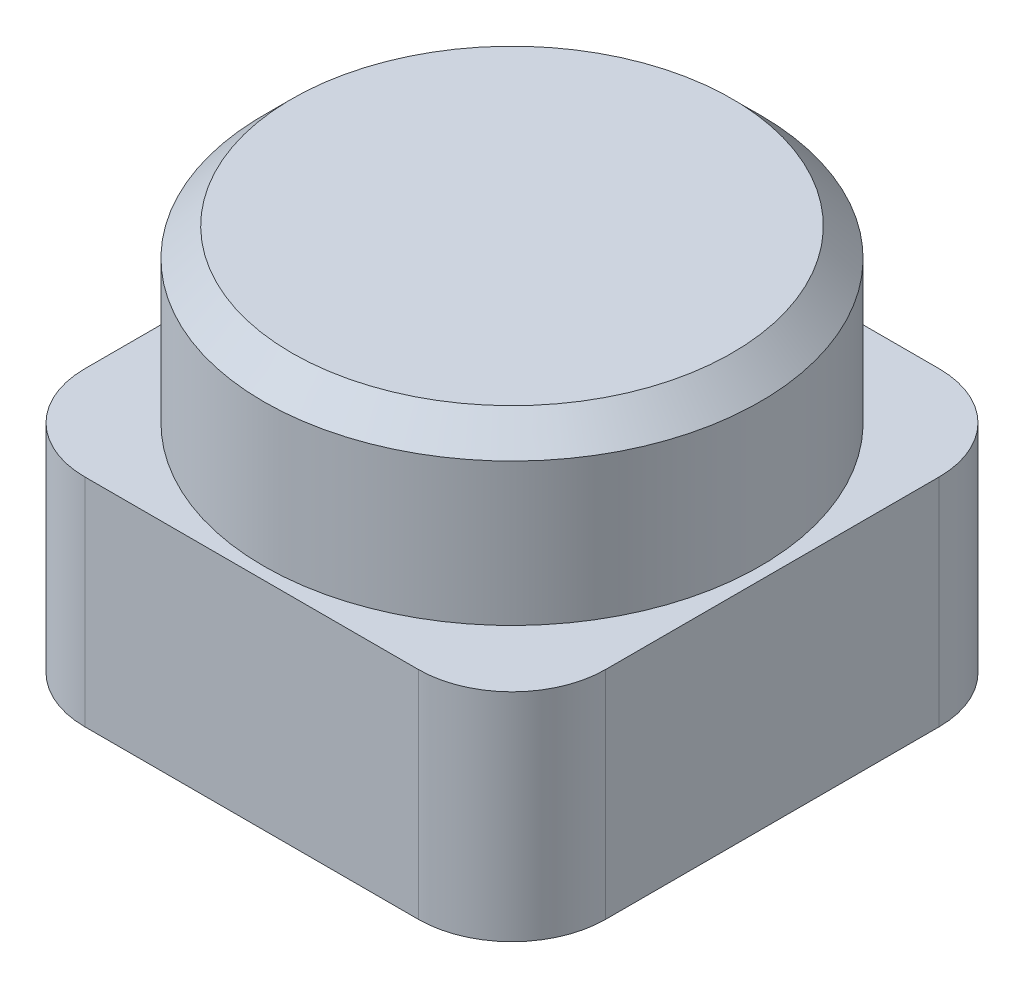
SolidWorks part; units mm, degrees
ref_plane "Front Plane" through (0, 0, 0) normal (0, 0, 1) x (1, 0, 0)
ref_plane "Top Plane" through (0, 0, 0) normal (0, 1, 0) x (1, 0, 0)
ref_plane "Right Plane" through (0, 0, 0) normal (1, 0, 0) x (0, 0, -1)
sketch "Sketch1" plane through (0, 0, 0) normal (0, 1, 0) x (1, 0, 0)
  line L1 (0, 0) -> (55.6, 0)
  line L2 (0, 0) -> (0, 55.6)
  line L3 (0, 55.6) -> (55.6, 55.6)
  line L4 (55.6, 0) -> (55.6, 55.6)
  dimension "D1" = 55.6
  dimension "D2" = 55.6
extrude "Boss-Extrude1" add sketch "Sketch1" along normal blind 23.1
fillet "Fillet1" radius 10 4 edges at (55.6, 11.55, -55.6) (0, 11.55, -55.6) (0, 11.55, 0) (55.6, 11.55, 0)
sketch "Sketch2" plane through (0, 0, 0) normal (0, -1, 0) x (1, 0, 0)
  line L0 (10, 0) -> (45.6, 0) construction
  line L1 (0, -45.6) -> (0, -10) construction
  line L2 (45.6, -55.6) -> (10, -55.6) construction
  line L3 (55.6, -10) -> (55.6, -45.6) construction
  circle A0 centre (6.3, -6.3) radius 1
  circle A1 centre (49.3, -6.3) radius 1
  circle A2 centre (49.3, -49.3) radius 1
  circle A3 centre (6.3, -49.3) radius 1
  point P12 (0, 0)
  point P17 (0, 0)
  point P18 (0, 0)
  point P19 (0, 0)
  point P20 (0, 0)
  point P21 (0, 0)
  dimension "D1" = 2
  dimension "D2" = 6.3
  dimension "D3" = 6.3
  dimension "D4" = 6.3
  dimension "D5" = 6.3
extrude "Screw Holes" cut sketch "Sketch2" against normal blind 4
sketch "Sketch3" plane through (0, 23.1, 0) normal (0, 1, 0) x (1, 0, 0)
  line L0 (45.6, 55.6) -> (10, 55.6) construction
  line L1 (27.8, 55.6) -> (27.8, 0) construction
  line L2 (10, 0) -> (45.6, 0) construction
  line L3 (0, 27.8) -> (55.6, 27.8) construction
  line L4 (0, 45.6) -> (0, 10) construction
  line L5 (55.6, 10) -> (55.6, 45.6) construction
  circle A0 centre (27.8, 27.8) radius 26.5
  dimension "D1" = 53
extrude "Boss-Extrude2" add sketch "Sketch3" along normal blind 18.2
chamfer "Chamfer1" distance 3 angle 45 1 edges at (27.8, 41.3, -1.3)
